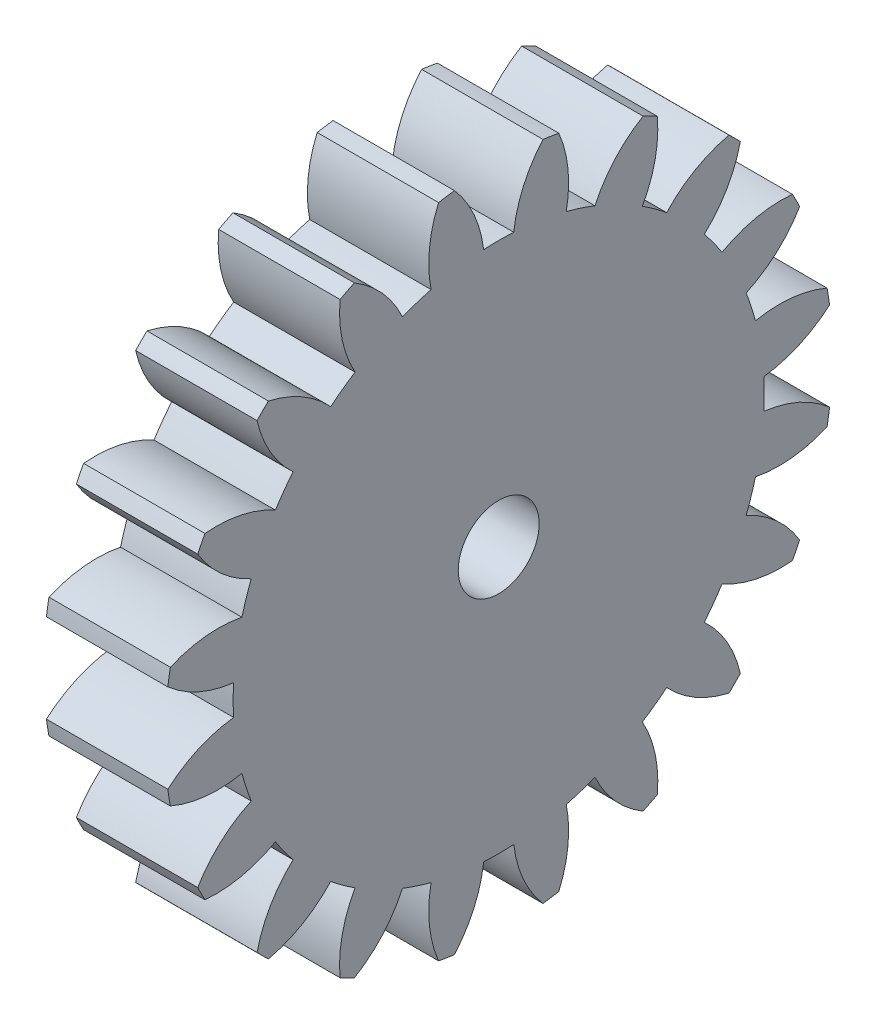
SolidWorks part; units mm, degrees
ref_plane "Plane1" through (0, 0, 0) normal (0, 0, 1) x (1, 0, 0)
ref_plane "Plane2" through (0, 0, 0) normal (0, 1, 0) x (1, 0, 0)
ref_plane "Plane3" through (0, 0, 0) normal (1, 0, 0) x (0, 0, -1)
other "Configuration Table"
sketch "HoldingSke" plane through (0, 0, 0) normal (0, 1, 0) x (1, 0, 0)
  line L0 (0, 0) -> (0.6265, -0.228)
  line L1 (-15, 0) -> (100, 0) construction
  line L2 (0, 0) -> (-2.1039, 2.3779)
  line L3 (0, 0) -> (-11.863, 4.5341)
  line L4 (0, 0) -> (8.1152, 2.9537)
  line L5 (0, 0) -> (-46.8476, -17.4728)
  line L6 (0, 0) -> (-4.9738, -3.3558)
  line L7 (-2.1039, 2.3779) -> (8.6586, 51.2059)
  line L8 (-76.2, 54.61) -> (-75.5, 54.61)
  line L9 (-71.009, 38.7566) -> (-53.1078, 45.2721)
  line L10 (-76.2, 71.12) -> (104.1128, 71.12)
  line L11 (0, 0) -> (-6, 0)
  line L12 (-76.2, 101.6) -> (-76.147, 101.6)
  line L13 (24.9733, 27.94) -> (52.9518, 28.4284)
  line L14 (24.9733, 27.94) -> (24.9743, 27.94)
  line L15 (24.9733, 27.94) -> (100.4006, 29.5858)
  line L16 (-63.627, -1.5) -> (-12.827, -1.5)
  circle A0 centre (0, 0) radius 2
  circle A1 centre (0, 0) radius 13.124
  circle A2 centre (0, 0) radius 37.5
  circle A3 centre (0, 0) radius 2
  dimension "MHD" = 26.248
  dimension "Hub_dia" = 75
  dimension "Bore" = 4
  dimension "MBD" = 4
  dimension "Num_teeth" = 20
  dimension "Pitch" = 0.6667
  dimension "Overall_len" = 50
  dimension "Show_teeth" = 20
  dimension "OAL" = 50.0001
  dimension "T_dim" = 0.7
  dimension "Ap" = 20
  dimension "H" = 19.05
  dimension "Pitch_radius" = 180.3128
  dimension "Backlash" = 0.053
  dimension "Addendum_fac" = 1
  dimension "Dedendum_fac" = 1.25
  dimension "Clearance_fac" = 0.25
  dimension "Dedendum_add" = 0.001
  dimension "Module" = 1.5
sketch "BasProSke" plane through (0, 0, 0) normal (0, 1, 0) x (1, 0, 0)
  line L0 (-10, 0) -> (60, 0) construction
  line L1 (0, 0) -> (0, 16.5)
  line L2 (0, 0) -> (6, 0)
  line L3 (6, 0) -> (6, 16.5)
  line L4 (6, 16.5) -> (0, 16.5)
  dimension "Diameter" = 33
revolve "Base-Revolve" add sketch "BasProSke" angle 360 about L0
sketch "TooCutSke" plane through (0, 0, 0) normal (1, 0, 0) x (0, 0, -1)
  line L1 (0, 0) -> (0, 107) construction
  line L2 (0, 0) -> (-1.2696, 14.9462) construction
  line L3 (0, 0) -> (-4.6808, 29.5532) construction
  line L4 (-1.2696, 14.9462) -> (-2.3404, 14.7766) construction
  arc A0 (0.7438, 13.1029) -> (-0.7438, 13.1029) centre (0, 0) ccw
  arc A1 (2.21, 16.377) -> (-2.21, 16.377) centre (0, 0) ccw
  circle A2 centre (0, 0) radius 15 construction
  circle A3 centre (0, 0) radius 14.0954 construction
  arc A4 (-0.7438, 13.1029) -> (-2.21, 16.377) centre (-6.7025, 12.3999) ccw
  arc A5 (2.21, 16.377) -> (0.7438, 13.1029) centre (6.7025, 12.3999) ccw
  dimension "Root_dia" = 26.248
  dimension "Overcut_dia" = 33.0508
  dimension "Pitch_dia" = 30
  dimension "Base_dia" = 28.1908
  dimension "Flank_rad" = 6
  dimension "Half_ang" = 9
  dimension "Half_CT" = 1.0841
extrude "ToothCut" cut sketch "TooCutSke" along normal through all
fillet "Breaks" [suppressed] radius 0.03
fillet "RootFillets" [suppressed] radius 0.376
pattern_circular "TeethCuts" count 20 every 18 about axis through (-10, 0, 0) along (1, 0, 0) of "ToothCut", "RootFillets", "Breaks"
sketch "HubNeaOneSke" plane through (0, 0, 0) normal (-1, 0, 0) x (0, 0, 1)
  circle A0 centre (0, 0) radius 13.124
  dimension "Diameter" = 26.248
extrude "HubNearOne" [suppressed] add sketch "HubNeaOneSke" along normal blind 44.0001
sketch "HubNeaBotSke" plane through (0, 0, 0) normal (-1, 0, 0) x (0, 0, 1)
  circle A0 centre (0, 0) radius 13.124
  dimension "Diameter" = 26.248
extrude "HubNearBoth" [suppressed] add sketch "HubNeaBotSke" along normal blind 22
ref_plane "FarPln" through (6, 0, 0) normal (1, 0, 0) x (0, 0, -1)
sketch "HubFarSke" plane through (6, 0, 0) normal (1, 0, 0) x (0, 0, -1)
  circle A0 centre (0, 0) radius 13.124
  dimension "Diameter" = 26.248
extrude "HubFar" [suppressed] add sketch "HubFarSke" along normal blind 22
sketch "BorSke" plane through (0, 0, 0) normal (1, 0, 0) x (0, 0, -1)
  circle A0 centre (0, 0) radius 2
  dimension "Diameter" = 4
extrude "Bore" cut sketch "BorSke" along normal mid plane 100.0001
sketch "KeySke" plane through (0, 0, 0) normal (1, 0, 0) x (0, 0, -1)
  line L0 (-0.8, 0) -> (-0.8, 2.7)
  line L1 (-0.8, 2.7) -> (0.8, 2.7)
  line L2 (0.8, 2.7) -> (0.8, 0)
  line L3 (0, 0) -> (0, 34) construction
  line L4 (-0.8, 0) -> (0.8, 0)
  dimension "Offset" = 2.7
  dimension "Width" = 1.6
extrude "Keyway" [suppressed] cut sketch "KeySke" along normal mid plane 100.0001
pattern_circular "Keyway2" [suppressed] count 2 every 90 about axis through (-10, 0, 0) along (1, 0, 0)
equation "' \"Module@HoldingSke\" = 6.35"
equation "' \"Num_teeth@HoldingSke\" = 12"
equation "' \"Ap@HoldingSke\" =  20"
equation "' \"Ap@HoldingSke\" = 20"
equation "' \"Width@HoldingSke\" = 0.5 * 25.4"
equation "' \"Hub_dia@HoldingSke\"= 1 * 25.4"
equation "' \"Hub_dia@HoldingSke\" = 1 * 25.4"
equation "' \"Overall_len@HoldingSke\" = 1.0 * 25.4"
equation "' \"Bore@HoldingSke\" = 0.75 * 25.4"
equation "' \"T_dim@HoldingSke\" = 0.1 * 25.4"
equation "' \"Width@KeySke\" = 0.25 * 25.4"
equation "' \"Show_teeth@HoldingSke\" = 13"
equation "' \"Backlash@HoldingSke\" = 0.009 * 25.4"
equation "' \"Addendum_fac@HoldingSke\" = 1.0"
equation "' \"Dedendum_fac@HoldingSke\" = 1.25"
equation "' \"Dedendum_add@HoldingSke\" = 0.00005 * 25.4"
equation "' \"Clearance_fac@HoldingSke\" = 0.25"
equation "\"Pitch@HoldingSke\" = 1 / \"Module@HoldingSke\""
equation "\"Overcut_dia@TooCutSke\" = (\"Num_teeth@HoldingSke\" + 2 * \"Addendum_fac@HoldingSke\") / \"Pitch@HoldingSke\" + 0.002 * 25.4"
equation "\"Pitch_dia@TooCutSke\" = \"Num_teeth@HoldingSke\" / \"Pitch@HoldingSke\""
equation "\"Base_dia@TooCutSke\" = \"Num_teeth@HoldingSke\" / \"Pitch@HoldingSke\" * cos((\"Ap@HoldingSke\"  * 3.14159265 / 180))"
equation "\"Root_dia@TooCutSke\" = (\"Num_teeth@HoldingSke\" + 2) / \"Pitch@HoldingSke\" - 2 * (\"Addendum_fac@HoldingSke\" + \"Dedendum_fac@HoldingSke\") / \"Pitch@HoldingSke\" - \"Dedendum_add@HoldingSke\" * 2"
equation "\"Half_ang@TooCutSke\" = 180 / \"Num_teeth@HoldingSke\""
equation "\"Half_CT@TooCutSke\" = \"Num_teeth@HoldingSke\" / \"Pitch@HoldingSke\" * sin((3.14159265 / 2 / \"Num_teeth@HoldingSke\")) / 2 - 7 * \"Backlash@HoldingSke\" / 4"
equation "\"Flank_rad@TooCutSke\" = \"Num_teeth@HoldingSke\" / \"Pitch@HoldingSke\" / 5"
equation "\"Radius@RootFillets\" = \"Clearance_fac@HoldingSke\" / \"Pitch@HoldingSke\" + \"Dedendum_add@HoldingSke\""
equation "\"Break_rad@Breaks\" = 0.02 / \"Pitch@HoldingSke\""
equation "\"Thickness@HoldingSke\" = \"Width@HoldingSke\""
equation "\"OAL@HoldingSke\" = \"Thickness@HoldingSke\""
equation "\"MHD@HoldingSke\" = (\"Num_teeth@HoldingSke\" + 2) / \"Pitch@HoldingSke\" - 2 * (\"Addendum_fac@HoldingSke\" + \"Dedendum_fac@HoldingSke\")  / \"Pitch@HoldingSke\" - \"Dedendum_add@HoldingSke\" * 2"
equation "\"MBD@HoldingSke\" = (\"Num_teeth@HoldingSke\" + 2) / \"Pitch@HoldingSke\" - 2 * (\"Addendum_fac@HoldingSke\" + \"Dedendum_fac@HoldingSke\")  / \"Pitch@HoldingSke\" - \"Dedendum_add@HoldingSke\" * 2 - 0.002 * 25.4"
equation "\"MHD@HoldingSke\" = ((sgn( \"MHD@HoldingSke\" - \"Hub_dia@HoldingSke\" )-1)*( \"MHD@HoldingSke\" - \"Hub_dia@HoldingSke\" ))/-2+ \"Hub_dia@HoldingSke\""
equation "\"MBD@HoldingSke\" = ((sgn( \"MBD@HoldingSke\" - \"Bore@HoldingSke\" )-1)*( \"MBD@HoldingSke\" - \"Bore@HoldingSke\" ))/-2+ \"Bore@HoldingSke\""
equation "\"OAL@HoldingSke\" = ((sgn( \"OAL@HoldingSke\" - \"Overall_len@HoldingSke\" )+1)*( \"OAL@HoldingSke\" - \"Overall_len@HoldingSke\" ))/2 + \"Overall_len@HoldingSke\" + 0.000002 * 25.4"
equation "\"Num_teeth@TeethCuts\" = int( \"Show_teeth@HoldingSke\" ) + 1"
equation "\"Num_teeth@TeethCuts\" = ((sgn( \"Num_teeth@TeethCuts\" - \"Num_teeth@HoldingSke\" )-1)*( \"Num_teeth@TeethCuts\" - \"Num_teeth@HoldingSke\" ))/-2+ \"Num_teeth@HoldingSke\""
equation "\"Num_teeth@TeethCuts\" = ((sgn( \"Num_teeth@TeethCuts\" - 2.0)+1)*( \"Num_teeth@TeethCuts\" - 2.0))/2 +2.0"
equation "\"Angle@TeethCuts\" = 360.0 / \"Num_teeth@HoldingSke\""
equation "\"Diameter@BasProSke\" = (\"Num_teeth@HoldingSke\" + 2 * \"Addendum_fac@HoldingSke\") / \"Pitch@HoldingSke\""
equation "\"Thickness@BasProSke\"  = \"Thickness@HoldingSke\""
equation "' \"Fillet_rad@BasProSke\" =  \"Thickness@HoldingSke\" * 0.05"
equation "' \"Fillet_rad@BasProSke\" = \"Thickness@HoldingSke\" * 0.05"
equation "\"MHD@HoldingSke\" = ((sgn( \"MHD@HoldingSke\" - \"Root_dia@TooCutSke\" )-1)*( \"MHD@HoldingSke\" - \"Root_dia@TooCutSke\" ))/-2+ \"Root_dia@TooCutSke\""
equation "\"Diameter@HubNeaOneSke\" = \"MHD@HoldingSke\""
equation "\"Length@HubNearOne\" = \"OAL@HoldingSke\" - \"Thickness@BasProSke\""
equation "\"Diameter@HubNeaBotSke\" = \"MHD@HoldingSke\""
equation "\"Length@HubNearBoth\" = ( \"OAL@HoldingSke\" - \"Thickness@BasProSke\" ) / 2.0"
equation "\"Thickness@FarPln\" = \"Thickness@BasProSke\""
equation "\"Diameter@HubFarSke\" = \"MHD@HoldingSke\""
equation "\"Length@HubFar\" = ( \"OAL@HoldingSke\" - \"Thickness@BasProSke\" ) / 2.0"
equation "\"Diameter@BorSke\" = \"MBD@HoldingSke\""
equation "\"D1@Bore\" = \"OAL@HoldingSke\" * 2.0"
equation "\"D1@Keyway\" = \"OAL@HoldingSke\" * 2.0"
equation "\"Offset@KeySke\" = \"T_dim@HoldingSke\" + \"MBD@HoldingSke\" / 2.0"
